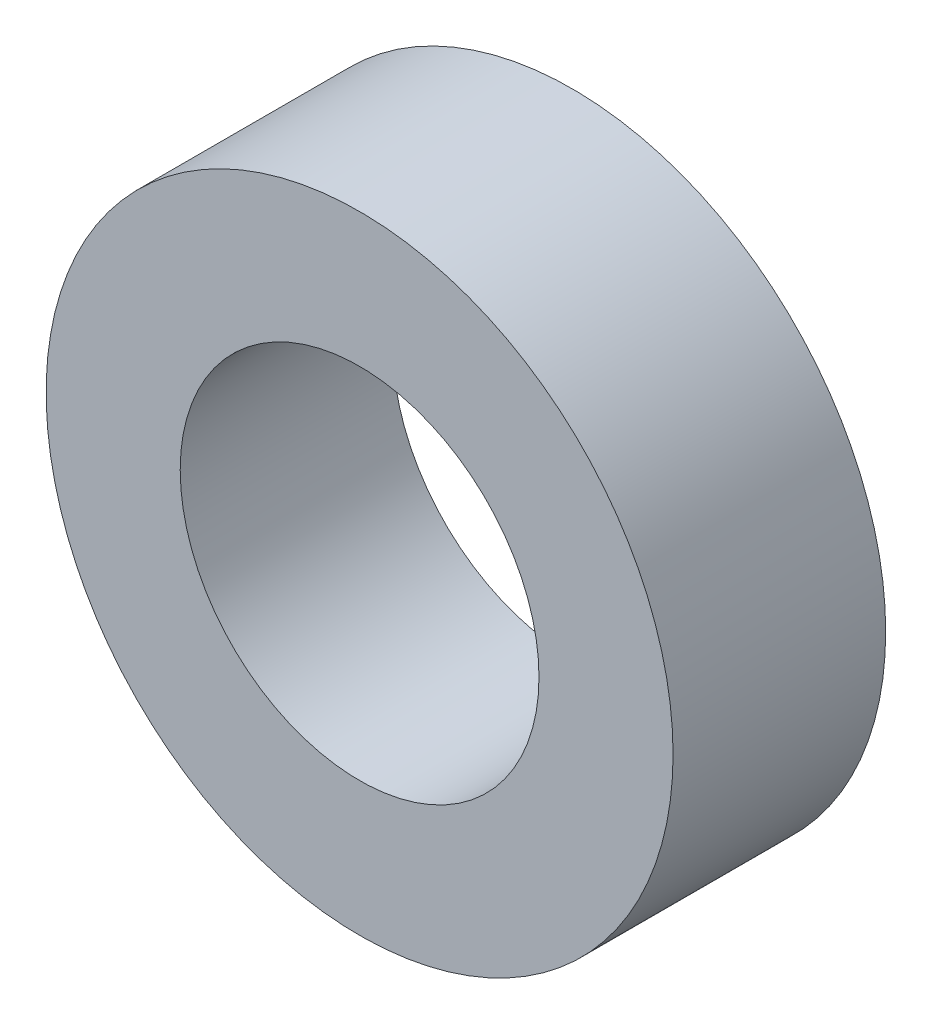
SolidWorks part; units mm, degrees
ref_plane "Plano frontal" through (0, 0, 0) normal (0, 0, 1) x (1, 0, 0)
ref_plane "Plano superior" through (0, 0, 0) normal (0, 1, 0) x (1, 0, 0)
ref_plane "Plano direito" through (0, 0, 0) normal (1, 0, 0) x (0, 0, -1)
sketch "Sketch1" plane through (0, 0, 0) normal (0, 0, 1) x (1, 0, 0)
  circle A0 centre (0, 0) radius 23.59
  circle A1 centre (0, 0) radius 13.5
extrude "Boss-Extrude1" add sketch "Sketch1" along normal blind 16
